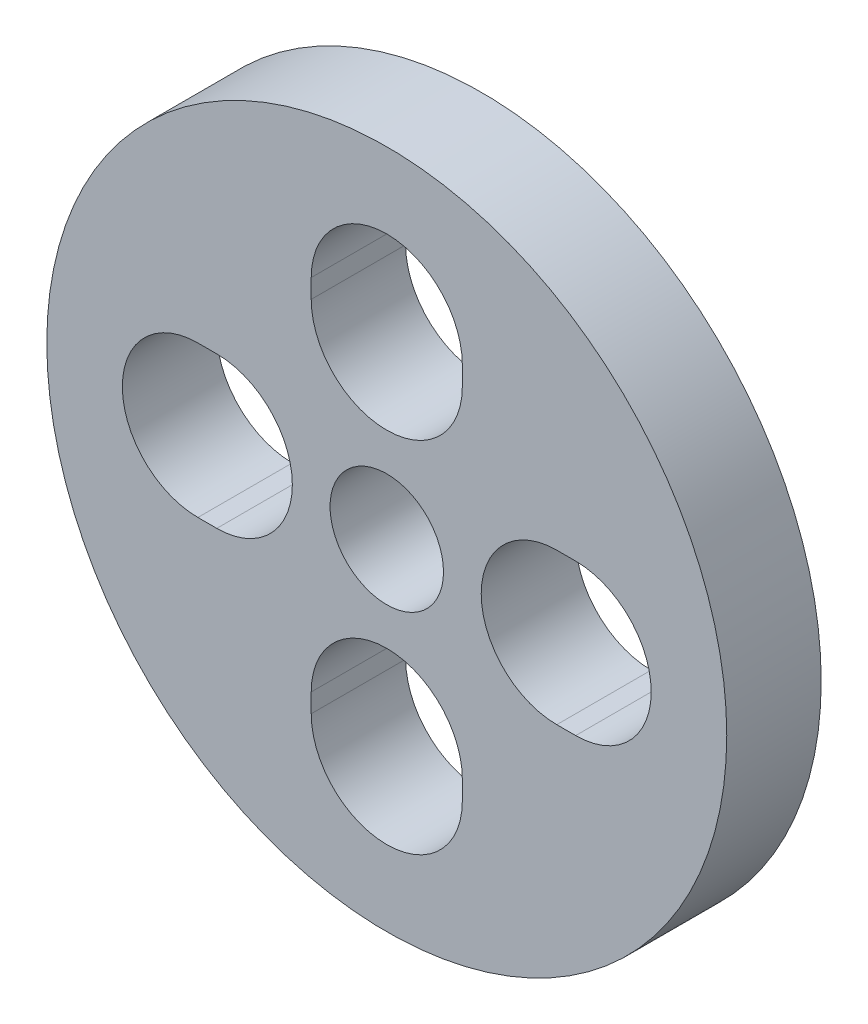
SolidWorks part; units mm, degrees
ref_plane "Plan de face" through (0, 0, 0) normal (0, 0, 1) x (1, 0, 0)
ref_plane "Plan de dessus" through (0, 0, 0) normal (0, 1, 0) x (1, 0, 0)
ref_plane "Plan de droite" through (0, 0, 0) normal (1, 0, 0) x (0, 0, -1)
sketch "Esquisse1" plane through (0, 0, 0) normal (0, 0, 1) x (1, 0, 0)
  circle A0 centre (0, 0) radius 18
  circle A1 centre (0, 0) radius 3.0025
  dimension "D1" = 36
  dimension "D2" = 6.005
extrude "Boss.-Extru.1" add sketch "Esquisse1" along normal blind 5
sketch "Esquisse2" plane through (0, 0, 5) normal (0, 0, 1) x (1, 0, 0)
  line L0 (0, 10) -> (0, 9) construction
  line L1 (4, 10) -> (4, 9)
  line L2 (-4, 10) -> (-4, 9)
  line L3 (10, 0) -> (9, 0) construction
  line L4 (10, -4) -> (9, -4)
  line L5 (10, 4) -> (9, 4)
  line L6 (0, -10) -> (0, -9) construction
  line L7 (-4, -10) -> (-4, -9)
  line L8 (4, -10) -> (4, -9)
  line L9 (-10, 0) -> (-9, 0) construction
  line L10 (-10, 4) -> (-9, 4)
  line L11 (-10, -4) -> (-9, -4)
  arc A0 (4, 10) -> (-4, 10) centre (0, 10) ccw
  arc A1 (-4, 9) -> (4, 9) centre (0, 9) ccw
  arc A2 (10, -4) -> (10, 4) centre (10, 0) ccw
  arc A3 (9, 4) -> (9, -4) centre (9, 0) ccw
  arc A4 (-4, -10) -> (4, -10) centre (0, -10) ccw
  circle A5 centre (0, 0) radius 18 construction
  arc A8 (4, -9) -> (-4, -9) centre (0, -9) ccw
  arc A9 (-10, 4) -> (-10, -4) centre (-10, 0) ccw
  arc A10 (-9, -4) -> (-9, 4) centre (-9, 0) ccw
  circle A11 centre (0, 0) radius 14
  circle A12 centre (0, 0) radius 5
  point P2 (0, 9.5)
  point P12 (0, 0)
  point P14 (9.5, 0)
  point P24 (0, -9.5)
  point P31 (-9.5, 0)
  point P36 (0, 0)
  dimension "D1" = 4
  dimension "D4" = 8
  dimension "D2" = 10
  dimension "D3" = 4
extrude "Enlèv. mat.-Extru.1" cut sketch "Esquisse2" against normal blind 5 contours L2 A1 L1 A0 | L11 A10 L10 A9 | L8 A8 L7 A4 | L5 A3 L4 A2
